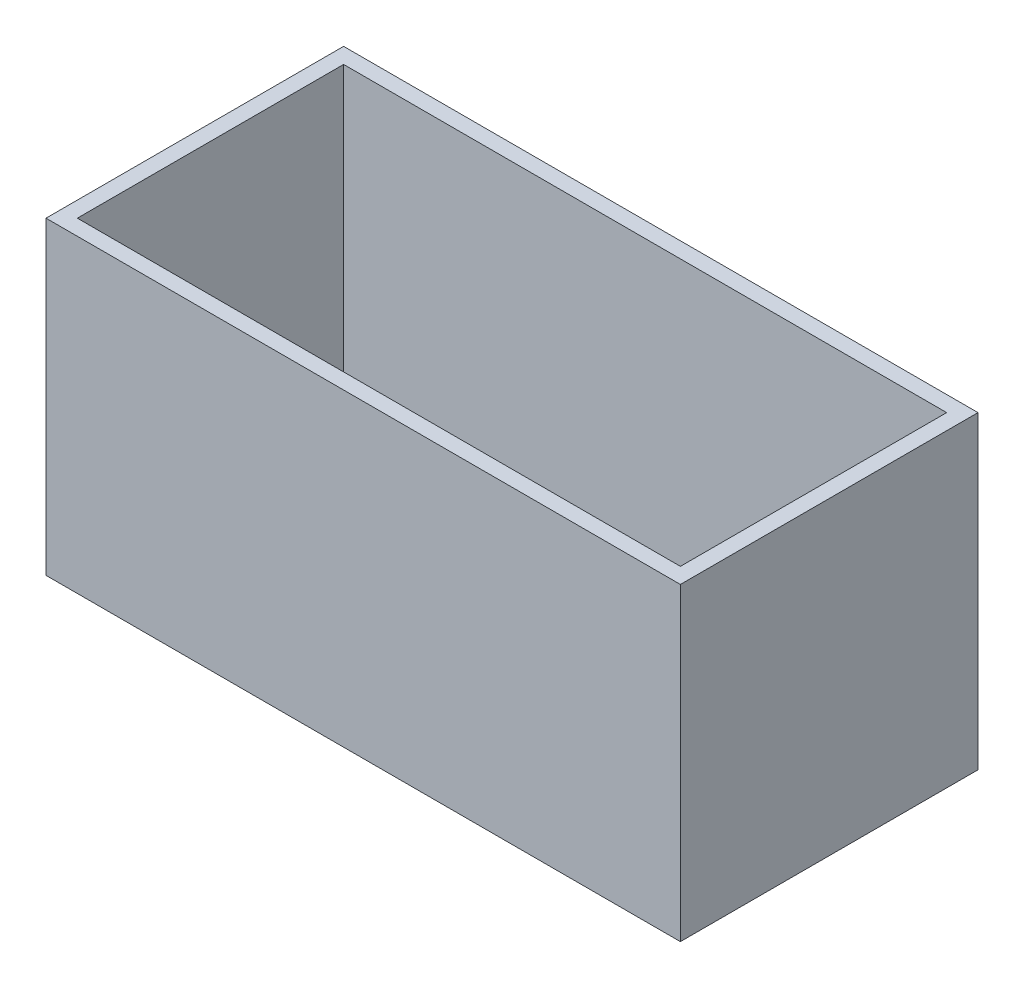
SolidWorks part; units mm, degrees
ref_plane "Front Plane" through (0, 0, 0) normal (0, 0, 1) x (1, 0, 0)
ref_plane "Top Plane" through (0, 0, 0) normal (0, 1, 0) x (1, 0, 0)
ref_plane "Right Plane" through (0, 0, 0) normal (1, 0, 0) x (0, 0, -1)
sketch "Sketch2" plane through (0, 0, 0) normal (0, 1, 0) x (1, 0, 0)
  line L1 (-102.87, -48.26) -> (102.87, -48.26)
  line L2 (-102.87, -48.26) -> (-102.87, 48.26)
  line L3 (-102.87, 48.26) -> (102.87, 48.26)
  line L4 (102.87, -48.26) -> (102.87, 48.26)
  line L5 (-102.87, -48.26) -> (102.87, 48.26) construction
  line L6 (-102.87, 48.26) -> (102.87, -48.26) construction
  point P0 (0, 0)
  point P11 (0, 40.5423)
  point P12 (0, 0)
  dimension "D1" = 205.74
  dimension "D2" = 96.52
extrude "Boss-Extrude1" add sketch "Sketch2" along normal blind 5.08
sketch "Sketch3" plane through (0, 5.08, 0) normal (0, 1, 0) x (1, 0, 0)
  line L4 (-102.87, 48.26) -> (102.87, 48.26)
  line L5 (102.87, 48.26) -> (102.87, -48.26)
  line L6 (102.87, -48.26) -> (-102.87, -48.26)
  line L7 (-102.87, -48.26) -> (-102.87, 48.26)
  line L8 (97.79, -43.18) -> (97.79, 43.18)
  line L9 (97.79, 43.18) -> (-97.79, 43.18)
  line L10 (-97.79, 43.18) -> (-97.79, -43.18)
  line L11 (-97.79, -43.18) -> (97.79, -43.18)
  line L12 (97.79, -43.18) -> (97.79, 43.18)
  line L13 (97.79, 43.18) -> (-97.79, 43.18)
  line L14 (-97.79, 43.18) -> (-97.79, -43.18)
  line L15 (-97.79, -43.18) -> (97.79, -43.18)
  dimension "D1" = 5.08
extrude "Boss-Extrude2" add sketch "Sketch3" along normal blind 95.25
sketch "Sketch5" plane through (0, 0, 0) normal (0, -1, 0) x (1, 0, 0)
  line L1 (-11.245, 41.207) -> (11.245, 41.207)
  line L2 (-11.245, 41.207) -> (-11.245, 32.9212)
  line L3 (-11.245, 32.9212) -> (11.245, 32.9212)
  line L4 (11.245, 41.207) -> (11.245, 32.9212)
  line L5 (-11.245, 41.207) -> (11.245, 32.9212) construction
  line L6 (-11.245, 32.9212) -> (11.245, 41.207) construction
  point P0 (0, 37.0641)
  point P5 (0, 37.0641)
extrude "Cut-Extrude1" cut sketch "Sketch5" against normal blind 95.25
